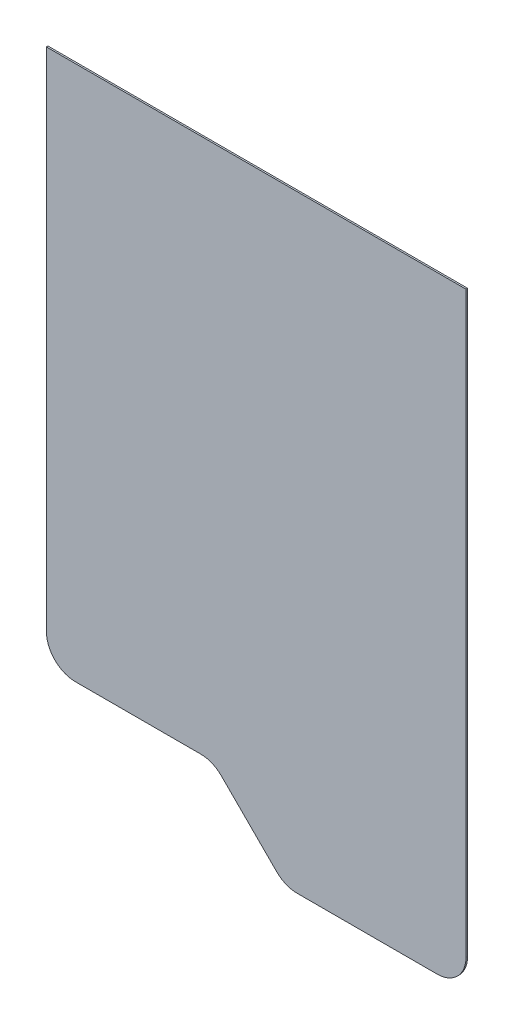
SolidWorks part; units mm, degrees
material "adhesive liner"
ref_plane "Front" through (0, 0, 0) normal (0, 0, 1) x (1, 0, 0)
ref_plane "Top" through (0, 0, 0) normal (0, 1, 0) x (1, 0, 0)
ref_plane "Right" through (0, 0, 0) normal (1, 0, 0) x (0, 0, -1)
sketch "Sketch3" plane through (0, 0, 0) normal (0, 0, 1) x (1, 0, 0)
  line L0 (0, 60) -> (0, -60) construction
  line L1 (-12.5, 60) -> (4.5, 60)
  line L2 (-14.5, 58) -> (-14.5, -58)
  line L3 (-12.5, -60) -> (12.5, -60)
  line L4 (14.5, 50) -> (14.5, -58)
  line L5 (-14.5, 60) -> (14.5, -60) construction
  line L6 (-14.5, -60) -> (14.5, 60) construction
  line L7 (-14.5, 0) -> (14.5, 0) construction
  line L8 (0, -50) -> (0, 50) construction
  line L9 (50, 0) -> (-50, 0) construction
  arc A0 (-14.5, -58) -> (-12.5, -60) centre (-12.5, -58) ccw
  arc A1 (12.5, -60) -> (14.5, -58) centre (12.5, -58) ccw
  arc A2 (4.5, 60) -> (14.5, 50) centre (4.5, 50) cw
  arc A3 (-12.5, 60) -> (-14.5, 58) centre (-12.5, 58) ccw
  point P0 (0, 0)
extrude "Boss-Extrude1" add sketch "Sketch3" along normal blind 0.11
sketch "Sketch4" plane through (0, 0, 0.11) normal (0, 0, 1) x (1, 0, 0)
  line L0 (-14.5, -23) -> (14.5, -23)
  line L1 (-14.5, 58) -> (-14.5, -58) construction
  line L2 (14.5, -58) -> (14.5, 50) construction
  line L3 (4.5, 60) -> (-12.5, 60) construction
  line L4 (14.5, -23) -> (14.5, 50)
  line L5 (4.5, 60) -> (-12.5, 60)
  line L6 (-14.5, 58) -> (-14.5, -23)
  line L9 (-12.5, -60) -> (12.5, -60) construction
  arc A0 (14.5, 50) -> (4.5, 60) centre (4.5, 50) ccw construction
  arc A1 (-12.5, 60) -> (-14.5, 58) centre (-12.5, 58) ccw construction
  arc A2 (14.5, 50) -> (4.5, 60) centre (4.5, 50) ccw
  arc A3 (-12.5, 60) -> (-14.5, 58) centre (-12.5, 58) ccw
  point P8 (3.5543, -60)
  dimension "D1" = 37
extrude "Cut-Extrude1" cut sketch "Sketch4" against normal through all
sketch "Sketch5" plane through (0, 0, 0.11) normal (0, 0, 1) x (1, 0, 0)
  line L0 (-12.5, -60) -> (12.5, -60) construction
  line L1 (14.5, -58) -> (14.5, -23) construction
  line L2 (-14.5, -23) -> (14.5, -23) construction
  line L3 (-14.5, -23) -> (-14.5, -58) construction
  line L4 (14.5, -63) -> (14.5, -23)
  line L5 (-14.5, -23) -> (14.5, -23)
  line L6 (-12.5, -60) -> (-3.8284, -60)
  line L8 (2.8284, -65) -> (12.5, -65)
  line L9 (-2.4142, -60.5858) -> (1.4142, -64.4142)
  line L10 (-14.5, -23) -> (-14.5, -58)
  arc A0 (-2.4142, -60.5858) -> (-3.8284, -60) centre (-3.8284, -62) ccw
  arc A1 (-14.5, -58) -> (-12.5, -60) centre (-12.5, -58) ccw construction
  arc A2 (-14.5, -58) -> (-12.5, -60) centre (-12.5, -58) ccw
  arc A5 (12.5, -65) -> (14.5, -63) centre (12.5, -63) ccw
  arc A6 (1.4142, -64.4142) -> (2.8284, -65) centre (2.8284, -63) ccw
  point P3 (0, -60)
  point P11 (-3, -60)
  dimension "D1" = 45
  dimension "D3" = 2
  dimension "D4" = 5
  dimension "D2" = 3
extrude "Boss-Extrude2" add sketch "Sketch5" against normal up to surface (0.11 mm away) up to face at (0, -47.1381, 0)
sketch "Sketch6" plane through (0, 0, 0.11) normal (0, 0, 1) x (1, 0, 0)
  circle A2 centre (0, -42) radius 3 construction
  circle A3 centre (0, -42) radius 3
extrude "Cut-Extrude2" [suppressed] cut sketch "Sketch6" against normal through all
